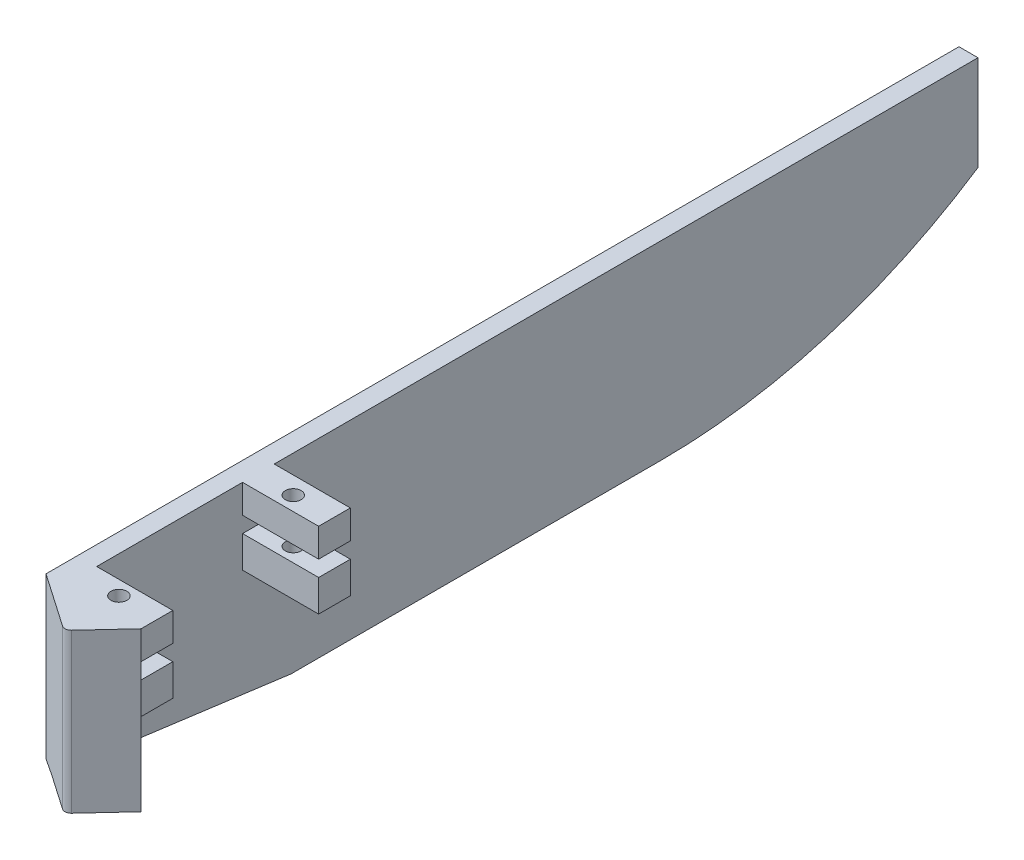
SolidWorks part; units mm, degrees
ref_plane "前视基准面" through (0, 0, 0) normal (0, 0, 1) x (1, 0, 0)
ref_plane "上视基准面" through (0, 0, 0) normal (0, 1, 0) x (1, 0, 0)
ref_plane "右视基准面" through (0, 0, 0) normal (1, 0, 0) x (0, 0, -1)
sketch "草图1" plane through (0, 0, 0) normal (1, 0, 0) x (0, 0, -1)
  line L1 (0, 0) -> (150, 0)
  line L2 (0, 0) -> (0, 30)
  line L3 (0, 30) -> (150, 30)
  line L4 (150, 0) -> (150, 30)
  dimension "D1" = 30
  dimension "D2" = 150
extrude "凸台-拉伸1" add sketch "草图1" along normal blind 3
sketch "草图2" plane through (3, 0, 0) normal (1, 0, 0) x (0, 0, -1)
  line L0 (150, 30) -> (0, 30) construction
  line L1 (6, 30) -> (11, 30)
  line L3 (6.0036, 25.5) -> (11, 25.5)
  line L4 (11, 30) -> (11, 25.5)
  line L5 (0, 30) -> (0, 0) construction
  line L6 (34, 30) -> (39, 30)
  line L7 (34, 30) -> (34, 25.5)
  line L8 (34, 25.5) -> (39, 25.5)
  line L9 (39, 30) -> (39, 25.5)
  line L10 (6.0036, 23) -> (11.0036, 23)
  line L12 (6.0036, 18) -> (11.0036, 18)
  line L13 (11.0036, 23) -> (11.0036, 18)
  line L14 (34.0036, 23) -> (39.0036, 23)
  line L15 (34.0036, 23) -> (34.0036, 18)
  line L16 (34.0036, 18) -> (39.0036, 18)
  line L17 (39.0036, 23) -> (39.0036, 18)
  line L18 (0, 0) -> (150, 0) construction
  line L19 (0, 30) -> (6, 30)
  line L20 (0, 30) -> (0, 0)
  line L21 (0, 0) -> (6.0036, 0)
  line L22 (6.0036, 25.5) -> (6.0036, 23)
  line L23 (6.0036, 18) -> (6.0036, 0)
  point P27 (0, 0)
  point P28 (0, 0)
  point P30 (0, 0)
  point P31 (0, 0)
  dimension "D1" = 4.5
  dimension "D2" = 4.5
  dimension "D3" = 5
  dimension "D4" = 5
  dimension "D5" = 2.5
  dimension "D6" = 23
  dimension "D7" = 5
  dimension "D8" = 23
  dimension "D9" = 5
  dimension "D10" = 5
  dimension "D11" = 5
  dimension "D12" = 11
  dimension "D13" = 6.0036
extrude "凸台-拉伸2" add sketch "草图2" along normal blind 12
sketch "草图3" plane through (0, 30, 0) normal (0, 1, 0) x (1, 0, 0)
  line L0 (15, 39) -> (15, 34) construction
  line L2 (15, 34) -> (3, 34) construction
  line L3 (15, 11) -> (3, 11) construction
  line L5 (15, 11) -> (15, 0) construction
  circle A0 centre (8.75, 36.25) radius 1.25
  circle A1 centre (8.75, 8.75) radius 1.25
  point P8 (11.2853, 50.5961)
  point P13 (15, 26.0567)
  dimension "D1" = 2.5
  dimension "D2" = 2.5
  dimension "D3" = 6.25
  dimension "D4" = 2.25
  dimension "D5" = 2.25
  dimension "D6" = 6.25
extrude "切除-拉伸1" cut sketch "草图3" against normal blind 12
sketch "草图5" plane through (0, 30, 0) normal (0, 1, 0) x (1, 0, 0)
  line L0 (15, 11) -> (15, 0) construction
  line L1 (15, 0) -> (0, 0) construction
  line L2 (15, 6) -> (9.7333, 0.3201)
  line L3 (0, 6) -> (8.4317, 0.1771)
  line L4 (0, 150) -> (0, 0) construction
  line L5 (15, 11) -> (3, 11) construction
  line L6 (0, 6) -> (0, 0)
  line L7 (0, 0) -> (9, 0)
  line L8 (15, 6) -> (15, 0)
  line L9 (15, 0) -> (9, 0)
  arc A0 (9.7333, 0.3201) -> (8.4317, 0.1771) centre (9, 1) cw
  line M6 (0, 150) -> (0, 0)
  line M7 (0, 0) -> (15, 0)
  line M8 (15, 0) -> (15, 11)
  dimension "D1" = 6
  dimension "D4" = 1
  dimension "D2" = 5
  dimension "D3" = 5
extrude "切除-拉伸2" cut sketch "草图5" against normal blind 33 contours A0 L3 M7 M6 | L2 A0 M7 M8
sketch "草图6" plane through (0, 0, -6.0036) normal (0, 0, -1) x (-1, 0, 0)
  line L0 (-3, 0) -> (-3, 18) construction
  line L1 (-15, 0) -> (-3, 0)
  line L2 (-15, 0) -> (-15, 5)
  line L3 (-15, 5) -> (-3, 5)
  line L4 (-3, 0) -> (-3, 5)
  dimension "D1" = 5
extrude "切除-拉伸3" cut sketch "草图6" against normal blind 14
sketch "草图7" plane through (3, 0, 0) normal (1, 0, 0) x (0, 0, -1)
  line L1 (3.9282, 0) -> (150, 0) construction
  line L2 (41.6596, 0) -> (3.9282, 0)
  line L3 (3.9282, 0) -> (3.9282, 5)
  line L4 (3.9282, 5) -> (41.6596, 0)
  point P7 (49.6096, 0)
  point P8 (41.6596, 0)
extrude "切除-拉伸4" cut sketch "草图7" against normal blind 14
sketch "草图8" plane through (3, 0, 0) normal (1, 0, 0) x (0, 0, -1)
  line L0 (150, 0) -> (150, 30) construction
  line L1 (41.6596, 0) -> (150, 0) construction
  line L2 (100, 0) -> (150, 0)
  line L3 (150, 0) -> (150, 15)
  arc A0 (150, 15) -> (100, 0) centre (100, 90.8333) cw
  point P3 (75.6704, 0)
  dimension "D1" = 15
  dimension "D2" = 50
extrude "切除-拉伸5" cut sketch "草图8" against normal blind 14
